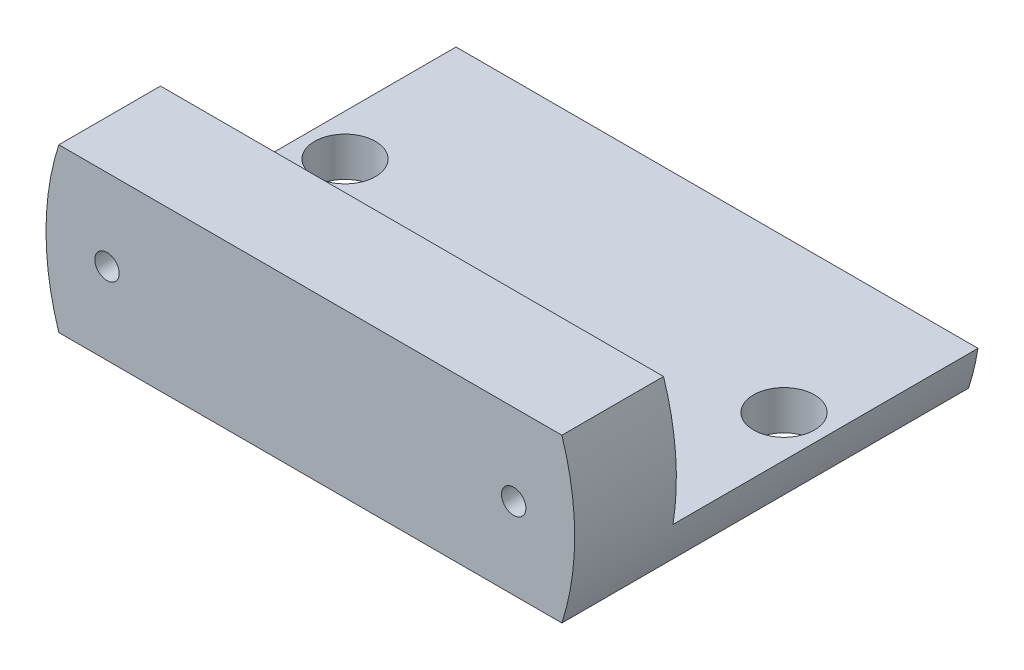
SolidWorks part; units mm, degrees
ref_plane "Front Plane" through (0, 0, 0) normal (0, 0, 1) x (1, 0, 0)
ref_plane "Top Plane" through (0, 0, 0) normal (0, 1, 0) x (1, 0, 0)
ref_plane "Right Plane" through (0, 0, 0) normal (1, 0, 0) x (0, 0, -1)
sketch "Sketch2" plane through (0, 0, 0) normal (0, 0, 1) x (1, 0, 0)
  line L0 (0, 0) -> (12.5, 0) construction
  line L1 (0, 0) -> (-12.5, 0) construction
  line L2 (0, 0) -> (0, 4) construction
  line L3 (0, 4) -> (-11.8427, 4) construction
  line L4 (-13.4164, 4) -> (11.8427, 4) construction
  line L5 (-11.8427, -4) -> (11.8427, -4) construction
  line L6 (-11.8427, 4) -> (11.8427, 4)
  line L7 (-11.8427, -4) -> (11.8427, -4)
  line L8 (0, 0) -> (0, 2) construction
  line L9 (0, 0) -> (10, 0) construction
  line L10 (0, 0) -> (0, -4) construction
  line L11 (-11.8427, 4) -> (-12.3693, 4)
  line L12 (11.8427, 4) -> (12.3693, 4)
  line L13 (-11.8427, -4) -> (-12.3693, -4)
  line L14 (11.8427, -4) -> (12.3693, -4)
  arc A0 (12.3693, -4) -> (12.3693, 4) centre (0, 0) ccw
  arc A1 (-12.3693, 4) -> (-12.3693, -4) centre (0, 0) ccw
  circle A2 centre (10, 0) radius 0.6
  circle A3 centre (-10, 0) radius 0.6
  point P11 (-13.4164, -4)
  point P12 (-13.4164, 4)
extrude "Boss-Extrude2" add sketch "Sketch2" along normal blind 5
ref_plane "Plane1" through (0, 4, 0) normal (0, 1, 0) x (1, 0, 0)
sketch "Sketch4" plane through (0, 4, 0) normal (0, 1, 0) x (1, 0, 0)
  line L0 (0, 0) -> (0, -5) construction
  line L1 (12.3693, 0) -> (-12.3693, 0) construction
  line L2 (12.3693, -5) -> (-12.3693, -5) construction
  line L3 (0, -2.5) -> (-10, -2.5) construction
ref_plane "Plane2" through (0, 0, 0) normal (0, 0, -1) x (-1, 0, 0)
sketch "Sketch7" plane through (0, 0, 0) normal (0, 0, -1) x (-1, 0, 0)
  line L0 (0, 0) -> (0, -4) construction
  line L1 (12.3693, -4) -> (-12.3693, -4) construction
  line L2 (0, 0) -> (0, 4) construction
  line L3 (0, -2.0689) -> (-12.3276, -2.0689)
  line L4 (0, -2.0689) -> (12.3276, -2.0689)
  line L5 (0, -4) -> (-11.8427, -4)
  line L6 (0, -4) -> (11.8427, -4)
  line L7 (0, 4) -> (10, 4) construction
  line L8 (12.3276, -2.0689) -> (12.8343, -2.0689)
  line L9 (11.8427, -4) -> (12.3693, -4)
  line L10 (-12.3276, -2.0689) -> (-12.8343, -2.0689)
  line L11 (-11.8427, -4) -> (-12.3693, -4)
  arc A0 (-12.8343, -2.0689) -> (-12.3693, -4) centre (0, 0) ccw
  arc A1 (12.3693, -4) -> (12.8343, -2.0689) centre (0, 0) ccw
extrude "Boss-Extrude4" add sketch "Sketch7" along normal blind 15
ref_plane "Plane4" through (0, -2.0689, 0) normal (0, 1, 0) x (1, 0, 0)
sketch "Sketch8" plane through (0, -2.0689, 0) normal (0, 1, 0) x (1, 0, 0)
  line L0 (0, 15) -> (0, 0) construction
  line L1 (-12.8343, 15) -> (12.8343, 15) construction
  line L2 (0, 15) -> (-8.2463, 15) construction
  line L3 (0, 7.5) -> (-8.255, 7.5) construction
  line L4 (0, 7.5) -> (-10.795, 7.5) construction
  circle A0 centre (-10.795, 7.5) radius 1.5
  circle A1 centre (10.795, 7.5) radius 1.5
extrude "Cut-Extrude2" cut sketch "Sketch8" against normal through all
